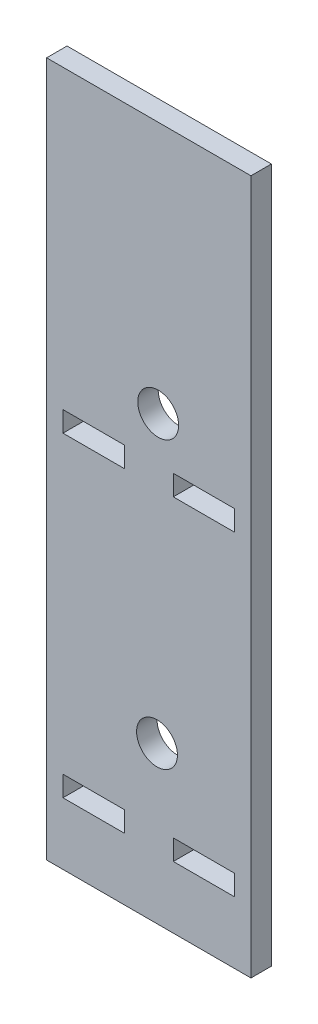
SolidWorks part; units mm, degrees
ref_plane "Front Plane" through (0, 0, 0) normal (0, 0, 1) x (1, 0, 0)
ref_plane "Top Plane" through (0, 0, 0) normal (0, 1, 0) x (1, 0, 0)
ref_plane "Right Plane" through (0, 0, 0) normal (1, 0, 0) x (0, 0, -1)
sketch "Sketch1" plane through (0, 0, 0) normal (0, 0, 1) x (1, 0, 0)
  line L0 (-17.7193, -8.2402) -> (-17.7193, 161.7598) construction
  line L1 (-42.7193, 6.9498) -> (7.2807, 6.9498) construction
  line L4 (-42.7193, -8.2402) -> (7.2807, -8.2402)
  line L5 (7.2807, -8.2402) -> (7.2807, 161.7598)
  line L6 (7.2807, 161.7598) -> (-42.7193, 161.7598)
  line L7 (-42.7193, 161.7598) -> (-42.7193, -8.2402)
  line L12 (-38.7193, 6.9498) -> (-38.7193, 11.9498)
  line L13 (-38.7193, 11.9498) -> (-23.7193, 11.9498)
  line L14 (-23.7193, 11.9498) -> (-23.7193, 6.9498)
  line L15 (-23.7193, 6.9498) -> (-38.7193, 6.9498)
  line L16 (-38.7193, 84.2166) -> (-23.7193, 84.2166)
  line L17 (-23.7193, 84.2166) -> (-23.7193, 89.2166)
  line L18 (-23.7193, 89.2166) -> (-38.7193, 89.2166)
  line L19 (-38.7193, 89.2166) -> (-38.7193, 84.2166)
  line L20 (3.2807, 84.2166) -> (-11.7193, 84.2166)
  line L21 (3.2807, 89.2166) -> (3.2807, 84.2166)
  line L22 (-11.7193, 89.2166) -> (3.2807, 89.2166)
  line L23 (-11.7193, 84.2166) -> (-11.7193, 89.2166)
  line L24 (-11.7193, 11.9498) -> (-11.7193, 6.9498)
  line L25 (3.2807, 6.9498) -> (3.2807, 11.9498)
  line L26 (3.2807, 11.9498) -> (-11.7193, 11.9498)
  line L27 (-11.7193, 6.9498) -> (3.2807, 6.9498)
  circle A0 centre (-15.7055, 29.9997) radius 5
  circle A1 centre (-15.4136, 99.9997) radius 5
  dimension "D3" = 10
  dimension "D4" = 10
  dimension "D1" = 50
  dimension "D2" = 70
  dimension "D5" = 170
  dimension "D6" = 5
  dimension "D7" = 15
  dimension "D8" = 6
  dimension "D9" = 5
extrude "Boss-Extrude1" add sketch "Sketch1" along normal blind 5
